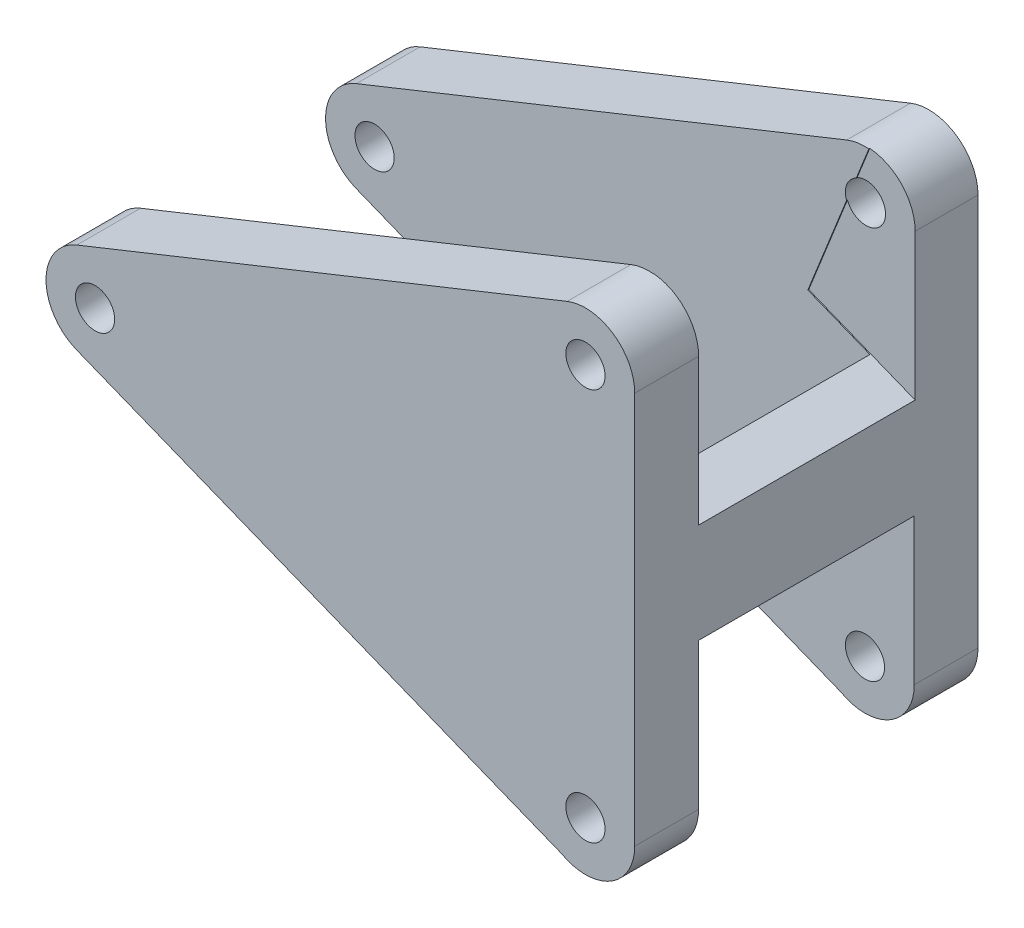
SolidWorks part; units mm, degrees
ref_plane "Ön Düzlem" through (0, 0, 0) normal (0, 0, 1) x (1, 0, 0)
ref_plane "Üst Düzlem" through (0, 0, 0) normal (0, 1, 0) x (1, 0, 0)
ref_plane "Sağ Düzlem" through (0, 0, 0) normal (1, 0, 0) x (0, 0, -1)
ref_plane "Düzlem1" through (0, 0, 28.5) normal (0, 0, 1) x (1, 0, 0)
sketch "Çizim1" plane through (0, 0, 28.5) normal (0, 0, 1) x (1, 0, 0)
  line L0 (35.0221, -20) -> (35.0221, 20)
  line L1 (30.5, 24.9972) -> (30.5, -24.9972)
  arc A0 (30.5, -24.9972) -> (35.0221, -20) centre (30, -20) ccw
  arc A1 (35.0221, 20) -> (30.5, 24.9972) centre (30, 20) ccw
extrude "Yükseklik-Ekstrüzyon1" add sketch "Çizim1" against normal blind 0.016
sketch "Çizim2" plane through (0, 0, 28.484) normal (0, 0, -1) x (-1, 0, 0)
  line L0 (-30.5, 24.9972) -> (-30.5, 6.9018)
  line L1 (-30.5, 6.9018) -> (-24.1725, 9.4297)
  line L2 (-24.1725, 9.4297) -> (-30.3956, 25.0065)
  line L3 (-28.1329, 24.6621) -> (21.8589, 4.6416)
  line L4 (21.857, -4.6424) -> (-27.5326, -24.3742)
  line L5 (-35.0221, -20) -> (-35.0221, 20)
  arc A0 (-30.3956, 25.0065) -> (-28.1329, 24.6621) centre (-30, 20) cw
  arc A1 (21.8589, 4.6416) -> (21.857, -4.6424) centre (20, 0) cw
  arc A2 (-27.5326, -24.3742) -> (-35.0221, -20) centre (-30, -20) cw
  arc A3 (-35.0221, 20) -> (-30.5, 24.9972) centre (-30, 20) cw
extrude "Yükseklik-Ekstrüzyon2" add sketch "Çizim2" along normal blind 22.0764
sketch "Çizim3" plane through (0, 0, 6.4076) normal (0, 0, -1) x (-1, 0, 0)
  line L0 (21.857, -4.6424) -> (-27.5326, -24.3742)
  line L1 (-35.0221, -20) -> (-35.0221, 20)
  line L2 (-28.1329, 24.6621) -> (21.8589, 4.6416)
  arc A0 (-27.5326, -24.3742) -> (-35.0221, -20) centre (-30, -20) cw
  arc A1 (-35.0221, 20) -> (-28.1329, 24.6621) centre (-30, 20) cw
  arc A2 (21.8589, 4.6416) -> (21.857, -4.6424) centre (20, 0) cw
extrude "Yükseklik-Ekstrüzyon3" add sketch "Çizim3" along normal blind 6.4076
sketch "Çizim4" plane through (0, 0, 28.5) normal (0, 0, 1) x (1, 0, 0)
  line L0 (27.5326, -24.3742) -> (-21.857, -4.6424)
  line L1 (-21.8589, 4.6416) -> (28.1329, 24.6621)
  line L2 (35.0221, 20) -> (35.0221, -20)
  arc A0 (-21.857, -4.6424) -> (-21.8589, 4.6416) centre (-20, 0) cw
  arc A1 (28.1329, 24.6621) -> (35.0221, 20) centre (30, 20) cw
  arc A2 (35.0221, -20) -> (27.5326, -24.3742) centre (30, -20) cw
extrude "Yükseklik-Ekstrüzyon4" add sketch "Çizim4" along normal blind 6.5
ref_plane "Düzlem2" through (0, 0, 6.4076) normal (0, 0, -1) x (-1, 0, 0)
sketch "Çizim5" plane through (0, 0, 6.4076) normal (0, 0, -1) x (-1, 0, 0)
  line L0 (-35.0221, 5.0952) -> (-30.5, 6.9018)
  line L1 (-30.5, 6.9018) -> (-30.5, 24.9972)
  line L2 (-35.0221, 20) -> (-35.0221, 5.0952)
  arc A0 (-30.5, 24.9972) -> (-35.0221, 20) centre (-30, 20) ccw
extrude "Kes-Ekstrüzyon1" cut sketch "Çizim5" against normal blind 22.0764
sketch "Çizim6" plane through (0, 0, 28.484) normal (0, 0, 1) x (1, 0, 0)
  line L0 (30.5, -24.9972) -> (30.5, 6.9018)
  line L1 (30.5, 6.9018) -> (24.1725, 9.4297)
  line L2 (24.1725, 9.4297) -> (30.3956, 25.0065)
  line L3 (28.1329, 24.6621) -> (-21.8589, 4.6416)
  line L4 (-21.857, -4.6424) -> (27.5326, -24.3742)
  arc A0 (27.5326, -24.3742) -> (30.5, -24.9972) centre (30, -20) ccw
  arc A1 (30.3956, 25.0065) -> (28.1329, 24.6621) centre (30, 20) ccw
  arc A2 (-21.8589, 4.6416) -> (-21.857, -4.6424) centre (-20, 0) ccw
extrude "Kes-Ekstrüzyon2" cut sketch "Çizim6" against normal blind 21.984
ref_plane "Düzlem3" through (0, 0, 6.5) normal (0, 0, -1) x (-1, 0, 0)
sketch "Çizim7" plane through (0, 0, 6.5) normal (0, 0, -1) x (-1, 0, 0)
  line L0 (-30.5, -24.9972) -> (-30.5, -6.8971)
  line L1 (-30.5, -6.8971) -> (-35.0221, -5.0861)
  line L2 (-35.0221, -5.0861) -> (-35.0221, -20)
  arc A0 (-35.0221, -20) -> (-30.5, -24.9972) centre (-30, -20) ccw
extrude "Kes-Ekstrüzyon3" cut sketch "Çizim7" against normal blind 21.9876
hole_wizard "Ø4.0 (4) Çap Delik1" positions "Çizim9" profile "Çizim8" hole size "Ø4.0" standard "ANSI Metric"
sketch "Çizim9" plane through (0, 0, 35) normal (0, 0, 1) x (1, 0, 0)
  point P0 (-20, 0)
sketch "Çizim8" plane through (-20, 0, 35) normal (1, 0, 0) x (0, -1, 0)
  line L0 (0, 0) -> (0, 6.5)
  line L1 (0, 6.5) -> (2, 6.5)
  line L2 (2, 6.5) -> (2, 0)
  line L5 (2, 0) -> (0, 0)
  line L11 (0, -6.35) -> (0, 107.95) construction
  dimension "Thru Hole Dia." = 4
  dimension "Thru Hole Depth" = 6.5
hole_wizard "Ø4.0 (4) Çap Delik2" positions "Çizim11" profile "Çizim10" hole size "Ø4.0" standard "ANSI Metric"
sketch "Çizim11" plane through (0, 0, 6.5) normal (0, 0, 1) x (1, 0, 0)
  point P0 (30, -20)
sketch "Çizim10" plane through (30, -20, 6.5) normal (1, 0, 0) x (0, -1, 0)
  line L0 (0, 0) -> (0, 6.5)
  line L1 (0, 6.5) -> (2, 6.5)
  line L2 (2, 6.5) -> (2, 0)
  line L5 (2, 0) -> (0, 0)
  line L11 (0, -6.35) -> (0, 107.95) construction
  dimension "Thru Hole Dia." = 4
  dimension "Thru Hole Depth" = 6.5
hole_wizard "Ø4.0 (4) Çap Delik3" positions "Çizim13" profile "Çizim12" hole size "Ø4.0" standard "ANSI Metric"
sketch "Çizim13" plane through (0, 0, 0) normal (0, 0, -1) x (-1, 0, 0)
  point P0 (-30, 20)
  point P1 (20, 0)
sketch "Çizim12" plane through (30, 20, 0) normal (1, 0, 0) x (0, 1, 0)
  line L0 (0, 0) -> (0, 6.4076)
  line L1 (0, 6.4076) -> (2, 6.4076)
  line L2 (2, 6.4076) -> (2, 0)
  line L5 (2, 0) -> (0, 0)
  line L11 (0, -6.35) -> (0, 107.95) construction
  dimension "Thru Hole Dia." = 4
  dimension "Thru Hole Depth" = 6.4076
hole_wizard "Ø4.0 (4) Çap Delik4" positions "Çizim15" profile "Çizim14" hole size "Ø4.0" standard "ANSI Metric"
sketch "Çizim15" plane through (0, 0, 35) normal (0, 0, 1) x (1, 0, 0)
  point P0 (30, -20)
  point P1 (30, 20)
sketch "Çizim14" plane through (30, -20, 35) normal (1, 0, 0) x (0, -1, 0)
  line L0 (0, 0) -> (0, 35)
  line L1 (0, 35) -> (2, 35)
  line L2 (2, 35) -> (2, 0)
  line L5 (2, 0) -> (0, 0)
  line L11 (0, -6.35) -> (0, 107.95) construction
  dimension "Thru Hole Dia." = 4
  dimension "Thru Hole Depth" = 35
